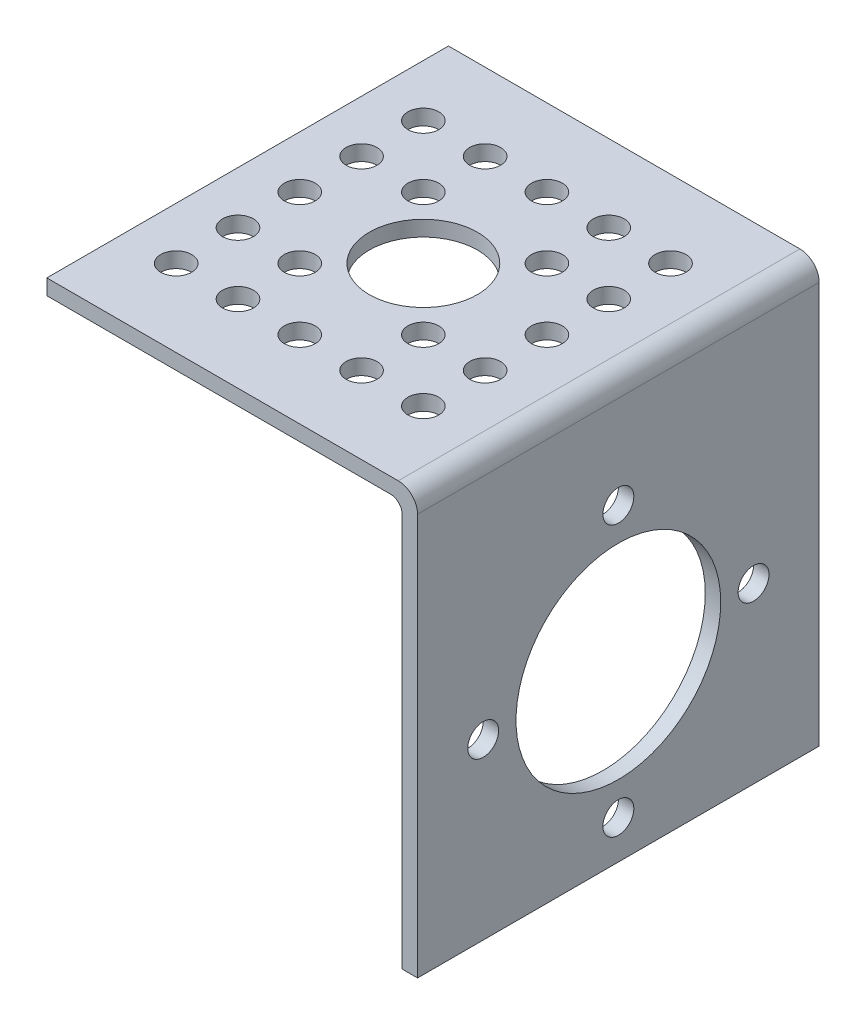
SolidWorks part; units mm, degrees
material "AISI 304"
ref_plane "前视基准面" through (0, 0, 0) normal (0, 0, 1) x (1, 0, 0)
ref_plane "上视基准面" through (0, 0, 0) normal (0, 1, 0) x (1, 0, 0)
ref_plane "右视基准面" through (0, 0, 0) normal (1, 0, 0) x (0, 0, -1)
sketch "Sketch1" plane through (0, 0, 0) normal (1, 0, 0) x (0, 0, -1)
  line L0 (0, 35.5166) -> (0, -50.5342) construction
  line L1 (-26, 30) -> (-26, -22.5)
  line L2 (26, 30) -> (26, -22.5)
  line L3 (-79.7434, 0) -> (87.5525, 0) construction
  line L4 (-26, -22.5) -> (26, -22.5)
  line L6 (-26, 30) -> (26, 30)
  line L8 (-26, 35.5166) -> (-26, -50.5342) construction
  line L9 (26, 35.5166) -> (26, -50.5342) construction
  line L10 (-79.7434, -22.5) -> (87.5525, -22.5) construction
  line L11 (-79.7434, 30) -> (87.5525, 30) construction
  circle A0 centre (0, 0) radius 17.5 construction
  circle A1 centre (0, 17.5) radius 2
  circle A2 centre (17.5, 0) radius 2
  circle A3 centre (0, -17.5) radius 2
  circle A4 centre (-17.5, 0) radius 2
  circle A5 centre (0, 0) radius 13.25
  point P13 (-79.7434, 22.5)
  point P14 (87.5525, 22.5)
  point P22 (0, 0)
  point P23 (-22.5, 35.8168)
  point P30 (0, 0)
  point P31 (22.5, 33.8672)
  dimension "D1" = 35
  dimension "D6" = 4
  dimension "D8" = 26.5
  dimension "D2" = 26
  dimension "D3" = 26
  dimension "D4" = 22.5
  dimension "D5" = 30
  dimension "D7" = 4
extrude "Boss-Extrude1" add sketch "Sketch1" along normal blind 2
sketch "Sketch3" plane through (2, 0, 0) normal (1, 0, 0) x (0, 0, -1)
  line L0 (-26, 30) -> (26, 30)
  line L1 (26, 30) -> (26, 32)
  line L2 (26, 32) -> (-26, 32)
  line L3 (-26, 32) -> (-26, 30)
  dimension "D1" = 2
extrude "Boss-Extrude3" add sketch "Sketch3" against normal blind 48
fillet "Fillet1" radius 1.5 1 edges at (0, 30, 0)
fillet "Fillet2" radius 2.5 1 edges at (2, 32, 0)
sketch "Sketch7" plane through (0, 32, 0) normal (0, 1, 0) x (1, 0, 0)
  line L0 (-46, 26) -> (-0.5, -26) construction
  line L1 (-0.5, 26) -> (-46, -26) construction
  line L2 (-23.25, 26.4714) -> (-23.25, -29.6602) construction
  line L3 (-39.25, 26.4714) -> (-39.25, -29.6602) construction
  line L4 (-7.25, 26.4714) -> (-7.25, -29.6602) construction
  line L5 (-74.7215, 0) -> (27.2439, 0) construction
  line L6 (-74.7215, -16) -> (27.2439, -16) construction
  line L7 (-74.7215, 16) -> (27.2439, 16) construction
  circle A0 centre (-23.25, 0) radius 7
  circle A1 centre (-39.25, 16) radius 2
  circle A2 centre (-31.25, 16) radius 2
  circle A3 centre (-23.25, 16) radius 2
  circle A4 centre (-15.25, 16) radius 2
  circle A5 centre (-7.25, 16) radius 2
  circle A6 centre (-31.25, 8) radius 2
  circle A8 centre (-15.25, 8) radius 2
  circle A9 centre (-7.25, 8) radius 2
  circle A13 centre (-7.25, 0) radius 2
  circle A14 centre (-31.25, -8) radius 2
  circle A16 centre (-15.25, -8) radius 2
  circle A17 centre (-7.25, -8) radius 2
  circle A18 centre (-31.25, -16) radius 2
  circle A19 centre (-23.25, -16) radius 2
  circle A20 centre (-15.25, -16) radius 2
  circle A21 centre (-7.25, -16) radius 2
  circle A22 centre (-39.25, 8) radius 2
  circle A23 centre (-39.25, 0) radius 2
  circle A24 centre (-39.25, -8) radius 2
  circle A25 centre (-39.25, -16) radius 2
  circle A26 centre (-31.25, 0) radius 2 [skipped]
  circle A27 centre (-23.25, 0) radius 2 [skipped]
  circle A28 centre (-23.25, 8) radius 2 [skipped]
  circle A29 centre (-15.25, 0) radius 2 [skipped]
  circle A30 centre (-23.25, -8) radius 2 [skipped]
  dimension "D1" = 14
  dimension "D6" = 4
  dimension "D2" = 16
  dimension "D3" = 16
  dimension "D4" = 16
  dimension "D5" = 16
  dimension "D7" = 5
  dimension "D8" = 5
extrude "Cut-Extrude1" cut sketch "Sketch7" against normal through all
